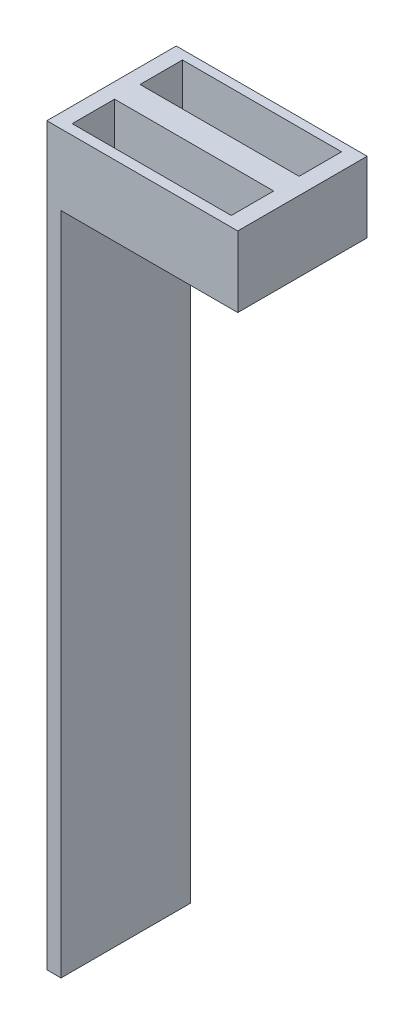
SolidWorks part; units mm, degrees
ref_plane "前视基准面" through (0, 0, 0) normal (0, 0, 1) x (1, 0, 0)
ref_plane "上视基准面" through (0, 0, 0) normal (0, 1, 0) x (1, 0, 0)
ref_plane "右视基准面" through (0, 0, 0) normal (1, 0, 0) x (0, 0, -1)
other "Configuration Table"
sketch "草图1" plane through (0, 0, 0) normal (0, 1, 0) x (1, 0, 0)
  line L1 (-13.5, -9.15) -> (13.5, -9.15)
  line L2 (-13.5, -9.15) -> (-13.5, 9.15)
  line L3 (-13.5, 9.15) -> (13.5, 9.15)
  line L4 (13.5, -9.15) -> (13.5, 9.15)
  line L5 (-13.5, -9.15) -> (13.5, 9.15) construction
  line L6 (-13.5, 9.15) -> (13.5, -9.15) construction
  point P0 (0, 0)
  dimension "D1" = 18.3
  dimension "D2" = 27
extrude "凸台-拉伸1" add sketch "草图1" along normal blind 10
sketch "草图2" plane through (0, 0, 0) normal (0, -1, 0) x (1, 0, 0)
  line L0 (13.5, -9.15) -> (-13.5, -9.15) construction
  line L1 (-11.35, -1.88) -> (11.15, -1.88)
  line L2 (-11.35, -1.88) -> (-11.35, -7.88)
  line L3 (-11.35, -7.88) -> (11.15, -7.88)
  line L4 (11.15, -1.88) -> (11.15, -7.88)
  line L5 (-11.35, 7.72) -> (11.15, 7.72)
  line L6 (-11.35, 7.72) -> (-11.35, 1.72)
  line L7 (-11.35, 1.72) -> (11.15, 1.72)
  line L8 (11.15, 7.72) -> (11.15, 1.72)
  line L9 (-13.5, -9.15) -> (-13.5, 9.15) construction
  dimension "D1" = 1.27
  dimension "D2" = 3.6
  dimension "D3" = 6
  dimension "D4" = 6
  dimension "D5" = 22.5
  dimension "D6" = 22.5
  dimension "D7" = 2.15
  dimension "D8" = 2.15
extrude "切除-拉伸1" cut sketch "草图2" against normal blind 10
sketch "草图3" plane through (0, 0, 0) normal (0, -1, 0) x (1, 0, 0)
  line L0 (13.5, -9.15) -> (-13.5, -9.15) construction
  line L1 (-13.5, 9.15) -> (-11.5, 9.15)
  line L2 (-13.5, 9.15) -> (-13.5, -9.15)
  line L3 (-13.5, -9.15) -> (-11.5, -9.15)
  line L4 (-11.5, 9.15) -> (-11.5, -9.15)
  dimension "D1" = 2
extrude "凸台-拉伸2" add sketch "草图3" along normal blind 94
